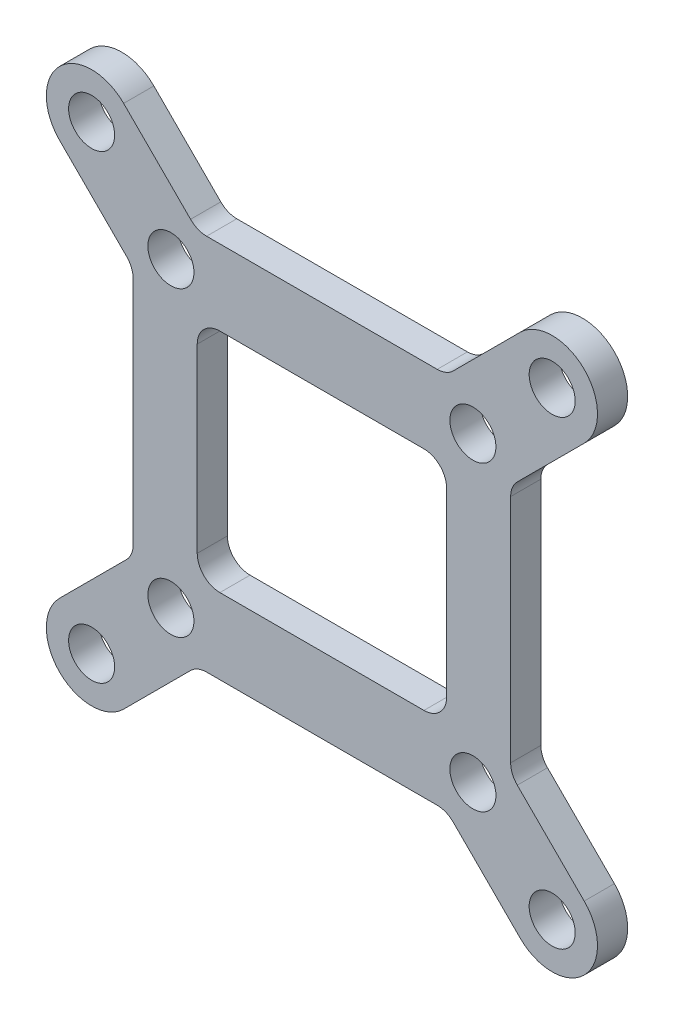
SolidWorks part; units mm, degrees
material "PA 类型 6"
ref_plane "前视基准面" through (0, 0, 0) normal (0, 0, 1) x (1, 0, 0)
ref_plane "上视基准面" through (0, 0, 0) normal (0, 1, 0) x (1, 0, 0)
ref_plane "右视基准面" through (0, 0, 0) normal (1, 0, 0) x (0, 0, -1)
sketch "草图1" plane through (0, 0, 0) normal (0, 0, 1) x (1, 0, 0)
  line L0 (0, 0) -> (-76.8397, 0) construction
  line L1 (0, 0) -> (0, 82.787) construction
  line L2 (0, 0) -> (-15.25, 15.25) construction
  line L3 (-8.2574, 12.5) -> (8.2574, 12.5)
  line L4 (-10, 10) -> (10, 10) construction
  line L5 (-8.2574, 12.5) -> (-13.1287, 17.3713)
  line L6 (-13.1287, 17.3713) -> (-15.25, 15.25) construction
  line L7 (-12.5, 8.2574) -> (-17.3713, 13.1287)
  line L8 (-8.2574, 7.5) -> (8.2574, 7.5)
  line L9 (12.5, -8.2574) -> (17.3713, -13.1287)
  line L10 (12.5, 8.2574) -> (17.3713, 13.1287)
  line L11 (8.2574, 12.5) -> (13.1287, 17.3713)
  line L12 (8.2574, -12.5) -> (13.1287, -17.3713)
  line L13 (-8.2574, -12.5) -> (8.2574, -12.5)
  line L14 (-8.2574, -12.5) -> (-13.1287, -17.3713)
  line L15 (-12.5, -8.2574) -> (-17.3713, -13.1287)
  line L16 (-12.5, 8.2574) -> (-12.5, -8.2574)
  line L17 (12.5, 8.2574) -> (12.5, -8.2574)
  line L18 (-8.2574, 7.5) -> (-8.2574, -7.5)
  line L19 (-8.2574, -7.5) -> (8.2574, -7.5)
  line L20 (8.2574, 7.5) -> (8.2574, -7.5)
  circle A0 centre (-15.25, 15.25) radius 1.525
  circle A1 centre (15.25, 15.25) radius 1.525
  circle A2 centre (-15.25, -15.25) radius 1.525
  circle A3 centre (15.25, -15.25) radius 1.525
  circle A4 centre (-10, 10) radius 1.525
  circle A5 centre (10, 10) radius 1.525
  circle A6 centre (10, -10) radius 1.525
  circle A7 centre (-10, -10) radius 1.525
  arc A8 (-17.3713, 13.1287) -> (-13.1287, 17.3713) centre (-15.25, 15.25) cw
  arc A9 (17.3713, 13.1287) -> (13.1287, 17.3713) centre (15.25, 15.25) ccw
  arc A10 (17.3713, -13.1287) -> (13.1287, -17.3713) centre (15.25, -15.25) cw
  arc A11 (-17.3713, -13.1287) -> (-13.1287, -17.3713) centre (-15.25, -15.25) ccw
  point P41 (-8.2574, 0)
  dimension "D5" = 3.05
  dimension "D1" = 30.5
  dimension "D2" = 30.5
  dimension "D3" = 20
  dimension "D4" = 20
  dimension "D6" = 6
  dimension "D7" = 2.5
extrude "凸台-拉伸1" add sketch "草图1" along normal blind 2
fillet "圆角1" radius 1.5 12 edges at (8.2574, -12.5, 1) (-8.2574, -12.5, 1) (12.5, -8.2574, 1) (12.5, 8.2574, 1) (8.2574, 12.5, 1) (-12.5, -8.2574, 1) (-12.5, 8.2574, 1) (-8.2574, 12.5, 1) (8.2574, -7.5, 1) (-8.2574, -7.5, 1) (-8.2574, 7.5, 1) (8.2574, 7.5, 1)
